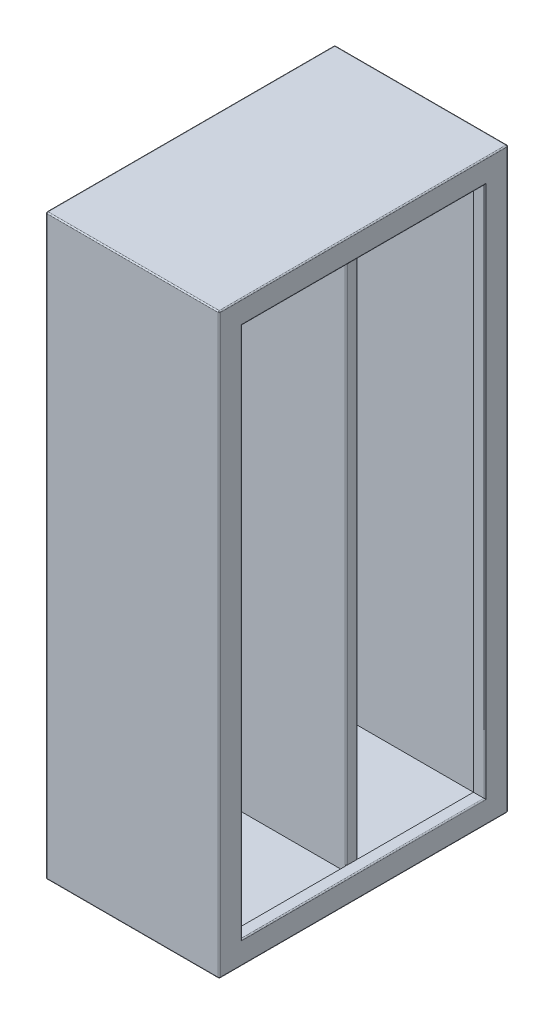
SolidWorks part; units mm, degrees
ref_plane "Front Plane" through (0, 0, 0) normal (1, 0, 0) x (0, 1, 0)
ref_plane "Top Plane" through (0, 0, 0) normal (0, 0, 1) x (0, 1, 0)
ref_plane "Right Plane" through (0, 0, 0) normal (0, 1, 0) x (-1, 0, 0)
sketch "Sketch1" plane through (0, 0, 0) normal (0, 0, 1) x (0, 1, 0)
  line L1 (-500, 0) -> (500, 0)
  line L2 (-500, 0) -> (-500, -300)
  line L3 (-500, -300) -> (500, -300)
  line L4 (500, 0) -> (500, -300)
  point P4 (0, 0)
  dimension "D1" = 1000
  dimension "D2" = 300
extrude "Boss-Extrude1" add sketch "Sketch1" along normal blind 500
shell "Shell1" thickness 40
sketch "Sketch3" plane through (40, 0, 0) normal (1, 0, 0) x (0, 1, 0)
  line L8 (-470, 30) -> (470, 30)
  line L9 (470, 30) -> (470, 470)
  line L10 (470, 470) -> (-470, 470)
  line L11 (-470, 470) -> (-470, 30)
  line L12 (-470, 30) -> (470, 30)
  line L13 (470, 30) -> (470, 470)
  line L14 (470, 470) -> (-470, 470)
  line L15 (-470, 470) -> (-470, 30)
  dimension "D1" = 10
extrude "Cut-Extrude1" cut sketch "Sketch3" along normal offset from surface (240 mm away) 20 up to face at (300, 0, 250)
sketch "Sketch4" plane through (40, 0, 0) normal (1, 0, 0) x (0, 1, 0)
  line L0 (0, 460) -> (0, 40) construction
  line L1 (-460, 460) -> (460, 460) construction
  line L2 (-460, 40) -> (460, 40) construction
  line L3 (470, 30) -> (470, 470) construction
  line L4 (-470, 240) -> (470, 240)
  line L5 (-470, 240) -> (-470, 260)
  line L6 (-470, 260) -> (470, 260)
  line L7 (470, 240) -> (470, 260)
  line L8 (-470, 240) -> (470, 260) construction
  line L9 (-470, 260) -> (470, 240) construction
  point P6 (0, 250)
  dimension "D1" = 20
extrude "Boss-Extrude2" add sketch "Sketch4" along normal offset from surface (240 mm away) 20 up to face at (300, 0, 250)
sketch "Sketch5" plane through (0, 460, 0) normal (0, -1, 0) x (1, 0, 0)
  line L0 (280, 240) -> (280, 40) construction
  line L1 (280, 60.4555) -> (300, 60.4555)
  line L2 (280, 60.4555) -> (280, 80.4555)
  line L3 (280, 80.4555) -> (300, 80.4555)
  line L4 (300, 60.4555) -> (300, 80.4555)
  line L5 (300, 460) -> (300, 40) construction
  line L6 (300, 40) -> (280, 40) construction
  dimension "D1" = 20
  dimension "D2" = 20.4555
extrude "Boss-Extrude3" [suppressed] add sketch "Sketch5" along normal blind 10
sketch "Sketch6" [suppressed] plane through (300, 0, 0) normal (1, 0, 0) x (0, 1, 0)
  line L1 (325, 80.4555) -> (335, 80.4555)
  line L2 (325, 80.4555) -> (325, 60.4555)
  line L3 (325, 60.4555) -> (335, 60.4555)
  line L4 (335, 80.4555) -> (335, 60.4555)
extrude "Boss-Extrude5" [suppressed] add sketch "Sketch6" along normal blind 10
sketch "Sketch7" [suppressed] plane through (0, 0, 80.4555) normal (0, 0, 1) x (1, 0, 0)
  circle A0 centre (310, 335) radius 5
  dimension "D1" = 10
extrude "Boss-Extrude6" [suppressed] add sketch "Sketch7" against normal blind 10
fillet "Fillet1" radius 2 18 edges at (150, -500, 0) (150, -500, 500) (150, 500, 500) (150, 500, 0) (0, 500, 250) (0, 0, 500) (0, -500, 250) (0, 0, 0) (300, 460, 250) (300, 0, 460) (300, -460, 250) (300, 0, 40) (300, -500, 250) (300, 0, 500) (300, 500, 250) (300, 0, 0) (280, 0, 240) (280, 0, 260)
